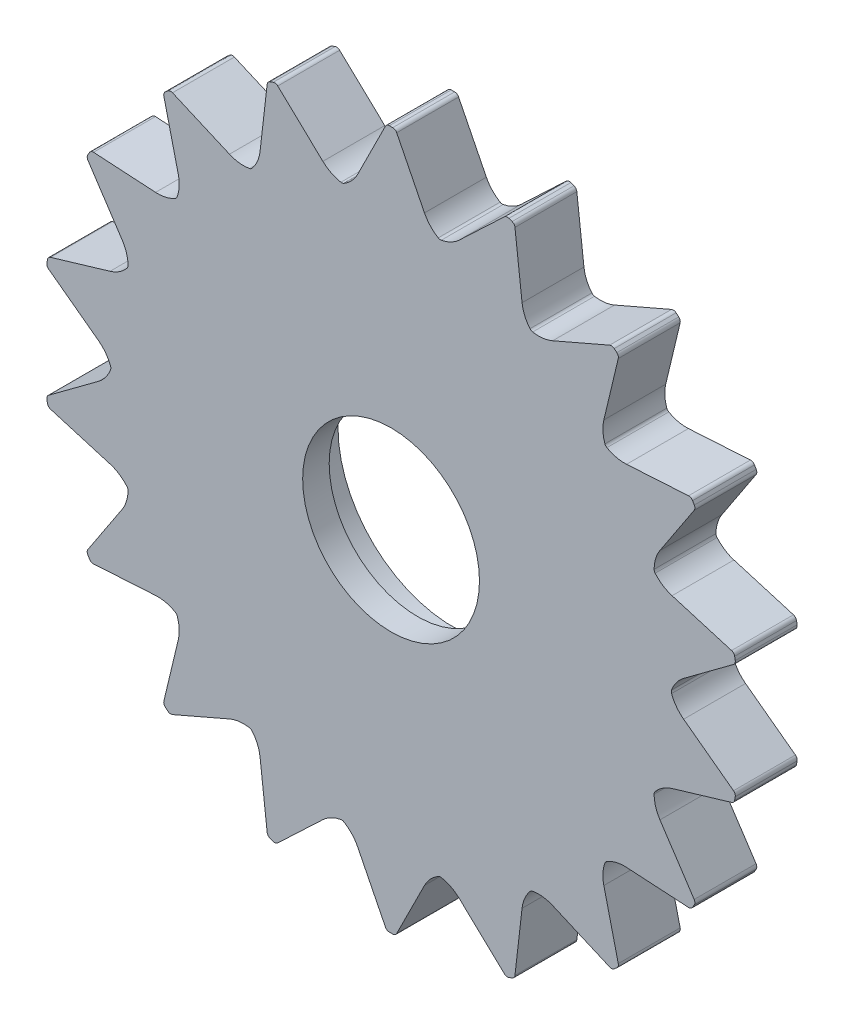
SolidWorks part; units mm, degrees
material "ASTM A36 Steel"
ref_plane "Front Plane" through (0, 0, 0) normal (0, 0, 1) x (1, 0, 0)
ref_plane "Top Plane" through (0, 0, 0) normal (0, 1, 0) x (1, 0, 0)
ref_plane "Right Plane" through (0, 0, 0) normal (1, 0, 0) x (0, 0, -1)
sketch "Sketch1" plane through (0, 0, 0) normal (0, 0, 1) x (1, 0, 0)
  line L0 (12.8152, 37.076) -> (7.7144, 32.2466)
  line L1 (14.8181, 29.661) -> (14.015, 36.6393)
  line L2 (24.7231, 30.457) -> (18.2781, 27.6634)
  line L3 (24.0692, 22.8041) -> (25.7012, 29.6363)
  line L4 (33.649, 20.1645) -> (26.6373, 19.7436)
  line L5 (3.7798, 32.9403) -> (0.6384, 39.2231)
  line L6 (-0.6384, 39.2231) -> (-3.7798, 32.9403)
  line L7 (30.4171, 13.1967) -> (34.2874, 19.0587)
  line L8 (38.5164, 7.4398) -> (31.7835, 9.4424)
  line L9 (33.0963, 1.9976) -> (38.7381, 6.1823)
  line L10 (38.7381, -6.1823) -> (33.0963, -1.9976)
  line L11 (31.7835, -9.4424) -> (38.5164, -7.4398)
  line L12 (34.2874, -19.0587) -> (30.4171, -13.1967)
  line L13 (26.6373, -19.7436) -> (33.649, -20.1645)
  line L14 (25.7012, -29.6363) -> (24.0692, -22.8041)
  line L15 (18.2781, -27.6634) -> (24.7231, -30.457)
  line L16 (14.015, -36.6393) -> (14.8181, -29.661)
  line L17 (7.7144, -32.2466) -> (12.8152, -37.076)
  line L18 (0.6384, -39.2231) -> (3.7798, -32.9403)
  line L19 (-3.7798, -32.9403) -> (-0.6384, -39.2231)
  line L20 (-12.8152, -37.076) -> (-7.7144, -32.2466)
  line L21 (-14.8181, -29.661) -> (-14.015, -36.6393)
  line L22 (-24.7231, -30.457) -> (-18.2781, -27.6634)
  line L23 (-24.0692, -22.8041) -> (-25.7012, -29.6363)
  line L24 (-33.649, -20.1645) -> (-26.6373, -19.7436)
  line L25 (-30.4171, -13.1967) -> (-34.2874, -19.0587)
  line L26 (-38.5164, -7.4398) -> (-31.7835, -9.4424)
  line L27 (-33.0963, -1.9976) -> (-38.7381, -6.1823)
  line L28 (-38.7381, 6.1823) -> (-33.0963, 1.9976)
  line L29 (-31.7835, 9.4424) -> (-38.5164, 7.4398)
  line L30 (-34.2874, 19.0587) -> (-30.4171, 13.1967)
  line L31 (-26.6373, 19.7436) -> (-33.649, 20.1645)
  line L32 (-25.7012, 29.6363) -> (-24.0692, 22.8041)
  line L33 (-18.2781, 27.6634) -> (-24.7231, 30.457)
  line L34 (-14.015, 36.6393) -> (-14.8181, 29.661)
  line L35 (-7.7144, 32.2466) -> (-12.8152, 37.076)
  circle A0 centre (0, 0) radius 10
  arc A3 (-0.6384, 39.2231) -> (-0.1937, 39.4995) centre (-0.1912, 38.9995) cw
  arc A4 (7.7144, 32.2466) -> (5.6805, 31.2158) centre (4.9643, 35.1512) cw
  arc A5 (0.1937, 39.4995) -> (-0.1937, 39.4995) centre (0, 0) ccw
  arc A6 (-3.7798, 32.9403) -> (-5.3386, 31.2761) centre (-7.3575, 34.7292) cw
  arc A7 (3.7798, 32.9403) -> (5.3386, 31.2761) centre (7.3575, 34.7292) ccw
  arc A8 (12.8152, 37.076) -> (13.3276, 37.1837) centre (13.1589, 36.713) cw
  arc A9 (13.6916, 37.0512) -> (13.3276, 37.1837) centre (0, 0) ccw
  arc A10 (13.6916, 37.0512) -> (14.015, 36.6393) centre (13.5183, 36.5822) cw
  arc A11 (14.8181, 29.661) -> (15.7137, 27.564) centre (18.7919, 30.1183) ccw
  arc A12 (15.7137, 27.564) -> (16.0143, 27.3905) centre (16.0984, 27.8833) ccw
  arc A13 (18.2781, 27.6634) -> (16.0143, 27.3905) centre (16.6873, 31.3334) cw
  arc A14 (24.7231, 30.457) -> (25.2414, 30.3829) centre (24.9219, 29.9983) cw
  arc A15 (25.5382, 30.1339) -> (25.2414, 30.3829) centre (0, 0) ccw
  arc A16 (25.5382, 30.1339) -> (25.7012, 29.6363) centre (25.2149, 29.7525) cw
  arc A17 (24.0692, 22.8041) -> (24.1935, 20.5273) centre (27.9597, 21.8748) ccw
  arc A18 (24.1935, 20.5273) -> (24.4166, 20.2614) centre (24.6643, 20.6958) ccw
  arc A19 (26.6373, 19.7436) -> (24.4166, 20.2614) centre (26.3976, 23.7364) cw
  arc A20 (33.649, 20.1645) -> (34.1108, 19.9175) centre (33.679, 19.6654) cw
  arc A21 (34.3044, 19.582) -> (34.1108, 19.9175) centre (0, 0) ccw
  arc A22 (34.3044, 19.582) -> (34.2874, 19.0587) centre (33.8702, 19.3342) cw
  arc A23 (30.4171, 13.1967) -> (29.7552, 11.0147) centre (33.7551, 10.9928) ccw
  arc A24 (29.7552, 11.0147) -> (29.8739, 10.6885) centre (30.2552, 11.012) ccw
  arc A25 (31.7835, 9.4424) -> (29.8739, 10.6885) centre (32.924, 13.2764) cw
  arc A26 (38.5164, 7.4398) -> (38.8658, 7.0497) centre (38.3738, 6.9605) cw
  arc A27 (38.9331, 6.6683) -> (38.8658, 7.0497) centre (0, 0) ccw
  arc A28 (38.9331, 6.6683) -> (38.7381, 6.1823) centre (38.4402, 6.5839) cw
  arc A29 (33.0963, 1.9976) -> (31.728, 0.1736) centre (35.4792, -1.2151) ccw
  arc A30 (31.728, 0.1736) -> (31.728, -0.1736) centre (32.1969, 0) ccw
  arc A31 (33.0963, -1.9976) -> (31.728, -0.1736) centre (35.4792, 1.2151) cw
  arc A32 (38.7381, -6.1823) -> (38.9331, -6.6683) centre (38.4402, -6.5839) cw
  arc A33 (38.8658, -7.0497) -> (38.9331, -6.6683) centre (0, 0) ccw
  arc A34 (38.8658, -7.0497) -> (38.5164, -7.4398) centre (38.3738, -6.9605) cw
  arc A35 (31.7835, -9.4424) -> (29.8739, -10.6885) centre (32.924, -13.2764) ccw
  arc A36 (29.8739, -10.6885) -> (29.7552, -11.0147) centre (30.2552, -11.012) ccw
  arc A37 (30.4171, -13.1967) -> (29.7552, -11.0147) centre (33.7551, -10.9928) cw
  arc A38 (34.2874, -19.0587) -> (34.3044, -19.582) centre (33.8702, -19.3342) cw
  arc A39 (34.1108, -19.9175) -> (34.3044, -19.582) centre (0, 0) ccw
  arc A40 (34.1108, -19.9175) -> (33.649, -20.1645) centre (33.679, -19.6654) cw
  arc A41 (26.6373, -19.7436) -> (24.4166, -20.2614) centre (26.3976, -23.7364) ccw
  arc A42 (24.4166, -20.2614) -> (24.1935, -20.5273) centre (24.6643, -20.6958) ccw
  arc A43 (24.0692, -22.8041) -> (24.1935, -20.5273) centre (27.9597, -21.8748) cw
  arc A44 (25.7012, -29.6363) -> (25.5382, -30.1339) centre (25.2149, -29.7525) cw
  arc A45 (25.2414, -30.3829) -> (25.5382, -30.1339) centre (0, 0) ccw
  arc A46 (25.2414, -30.3829) -> (24.7231, -30.457) centre (24.9219, -29.9983) cw
  arc A47 (18.2781, -27.6634) -> (16.0143, -27.3905) centre (16.6873, -31.3334) ccw
  arc A48 (16.0143, -27.3905) -> (15.7137, -27.564) centre (16.0984, -27.8833) ccw
  arc A49 (14.8181, -29.661) -> (15.7137, -27.564) centre (18.7919, -30.1183) cw
  arc A50 (14.015, -36.6393) -> (13.6916, -37.0512) centre (13.5183, -36.5822) cw
  arc A51 (13.3276, -37.1837) -> (13.6916, -37.0512) centre (0, 0) ccw
  arc A52 (13.3276, -37.1837) -> (12.8152, -37.076) centre (13.1589, -36.713) cw
  arc A53 (7.7144, -32.2466) -> (5.6805, -31.2158) centre (4.9643, -35.1512) ccw
  arc A54 (5.6805, -31.2158) -> (5.3386, -31.2761) centre (5.5909, -31.7078) ccw
  arc A55 (3.7798, -32.9403) -> (5.3386, -31.2761) centre (7.3575, -34.7292) cw
  arc A56 (0.6384, -39.2231) -> (0.1937, -39.4995) centre (0.1912, -38.9995) cw
  arc A57 (-0.1937, -39.4995) -> (0.1937, -39.4995) centre (0, 0) ccw
  arc A58 (0.1937, 39.4995) -> (0.6384, 39.2231) centre (0.1912, 38.9995) cw
  arc A59 (5.3386, 31.2761) -> (5.6805, 31.2158) centre (5.5909, 31.7078) ccw
  arc A60 (-0.1937, -39.4995) -> (-0.6384, -39.2231) centre (-0.1912, -38.9995) cw
  arc A61 (-3.7798, -32.9403) -> (-5.3386, -31.2761) centre (-7.3575, -34.7292) ccw
  arc A62 (-5.3386, -31.2761) -> (-5.6805, -31.2158) centre (-5.5909, -31.7078) ccw
  arc A63 (-7.7144, -32.2466) -> (-5.6805, -31.2158) centre (-4.9643, -35.1512) cw
  arc A64 (-12.8152, -37.076) -> (-13.3276, -37.1837) centre (-13.1589, -36.713) cw
  arc A65 (-13.6916, -37.0512) -> (-13.3276, -37.1837) centre (0, 0) ccw
  arc A66 (-13.6916, -37.0512) -> (-14.015, -36.6393) centre (-13.5183, -36.5822) cw
  arc A67 (-14.8181, -29.661) -> (-15.7137, -27.564) centre (-18.7919, -30.1183) ccw
  arc A68 (-15.7137, -27.564) -> (-16.0143, -27.3905) centre (-16.0984, -27.8833) ccw
  arc A69 (-18.2781, -27.6634) -> (-16.0143, -27.3905) centre (-16.6873, -31.3334) cw
  arc A70 (-24.7231, -30.457) -> (-25.2414, -30.3829) centre (-24.9219, -29.9983) cw
  arc A71 (-25.5382, -30.1339) -> (-25.2414, -30.3829) centre (0, 0) ccw
  arc A72 (-25.5382, -30.1339) -> (-25.7012, -29.6363) centre (-25.2149, -29.7525) cw
  arc A73 (-24.0692, -22.8041) -> (-24.1935, -20.5273) centre (-27.9597, -21.8748) ccw
  arc A74 (-24.1935, -20.5273) -> (-24.4166, -20.2614) centre (-24.6643, -20.6958) ccw
  arc A75 (-26.6373, -19.7436) -> (-24.4166, -20.2614) centre (-26.3976, -23.7364) cw
  arc A76 (-33.649, -20.1645) -> (-34.1108, -19.9175) centre (-33.679, -19.6654) cw
  arc A77 (-34.3044, -19.582) -> (-34.1108, -19.9175) centre (0, 0) ccw
  arc A78 (-34.3044, -19.582) -> (-34.2874, -19.0587) centre (-33.8702, -19.3342) cw
  arc A79 (-30.4171, -13.1967) -> (-29.7552, -11.0147) centre (-33.7551, -10.9928) ccw
  arc A80 (-29.7552, -11.0147) -> (-29.8739, -10.6885) centre (-30.2552, -11.012) ccw
  arc A81 (-31.7835, -9.4424) -> (-29.8739, -10.6885) centre (-32.924, -13.2764) cw
  arc A82 (-38.5164, -7.4398) -> (-38.8658, -7.0497) centre (-38.3738, -6.9605) cw
  arc A83 (-38.9331, -6.6683) -> (-38.8658, -7.0497) centre (0, 0) ccw
  arc A84 (-38.9331, -6.6683) -> (-38.7381, -6.1823) centre (-38.4402, -6.5839) cw
  arc A85 (-33.0963, -1.9976) -> (-31.728, -0.1736) centre (-35.4792, 1.2151) ccw
  arc A86 (-31.728, -0.1736) -> (-31.728, 0.1736) centre (-32.1969, 0) ccw
  arc A87 (-33.0963, 1.9976) -> (-31.728, 0.1736) centre (-35.4792, -1.2151) cw
  arc A88 (-38.7381, 6.1823) -> (-38.9331, 6.6683) centre (-38.4402, 6.5839) cw
  arc A89 (-38.8658, 7.0497) -> (-38.9331, 6.6683) centre (0, 0) ccw
  arc A90 (-38.8658, 7.0497) -> (-38.5164, 7.4398) centre (-38.3738, 6.9605) cw
  arc A91 (-31.7835, 9.4424) -> (-29.8739, 10.6885) centre (-32.924, 13.2764) ccw
  arc A92 (-29.8739, 10.6885) -> (-29.7552, 11.0147) centre (-30.2552, 11.012) ccw
  arc A93 (-30.4171, 13.1967) -> (-29.7552, 11.0147) centre (-33.7551, 10.9928) cw
  arc A94 (-34.2874, 19.0587) -> (-34.3044, 19.582) centre (-33.8702, 19.3342) cw
  arc A95 (-34.1108, 19.9175) -> (-34.3044, 19.582) centre (0, 0) ccw
  arc A96 (-34.1108, 19.9175) -> (-33.649, 20.1645) centre (-33.679, 19.6654) cw
  arc A97 (-26.6373, 19.7436) -> (-24.4166, 20.2614) centre (-26.3976, 23.7364) ccw
  arc A98 (-24.4166, 20.2614) -> (-24.1935, 20.5273) centre (-24.6643, 20.6958) ccw
  arc A99 (-24.0692, 22.8041) -> (-24.1935, 20.5273) centre (-27.9597, 21.8748) cw
  arc A100 (-25.7012, 29.6363) -> (-25.5382, 30.1339) centre (-25.2149, 29.7525) cw
  arc A101 (-25.2414, 30.3829) -> (-25.5382, 30.1339) centre (0, 0) ccw
  arc A102 (-25.2414, 30.3829) -> (-24.7231, 30.457) centre (-24.9219, 29.9983) cw
  arc A103 (-18.2781, 27.6634) -> (-16.0143, 27.3905) centre (-16.6873, 31.3334) ccw
  arc A104 (-16.0143, 27.3905) -> (-15.7137, 27.564) centre (-16.0984, 27.8833) ccw
  arc A105 (-14.8181, 29.661) -> (-15.7137, 27.564) centre (-18.7919, 30.1183) cw
  arc A106 (-14.015, 36.6393) -> (-13.6916, 37.0512) centre (-13.5183, 36.5822) cw
  arc A107 (-13.3276, 37.1837) -> (-13.6916, 37.0512) centre (0, 0) ccw
  arc A108 (-13.3276, 37.1837) -> (-12.8152, 37.076) centre (-13.1589, 36.713) cw
  arc A109 (-7.7144, 32.2466) -> (-5.6805, 31.2158) centre (-4.9643, 35.1512) ccw
  arc A110 (-5.6805, 31.2158) -> (-5.3386, 31.2761) centre (-5.5909, 31.7078) ccw
  point P188 (0, 0)
  point P261 (0, 0)
  dimension "D1" = 18
extrude "Boss-Extrude1" add sketch "Sketch1" along normal blind 7
sketch "Sketch2" plane through (0, 0, 0) normal (0, 0, -1) x (-1, 0, 0)
  circle A0 centre (0, 0) radius 13
  dimension "D1" = 26
extrude "Cut-Extrude1" cut sketch "Sketch2" against normal blind 4
